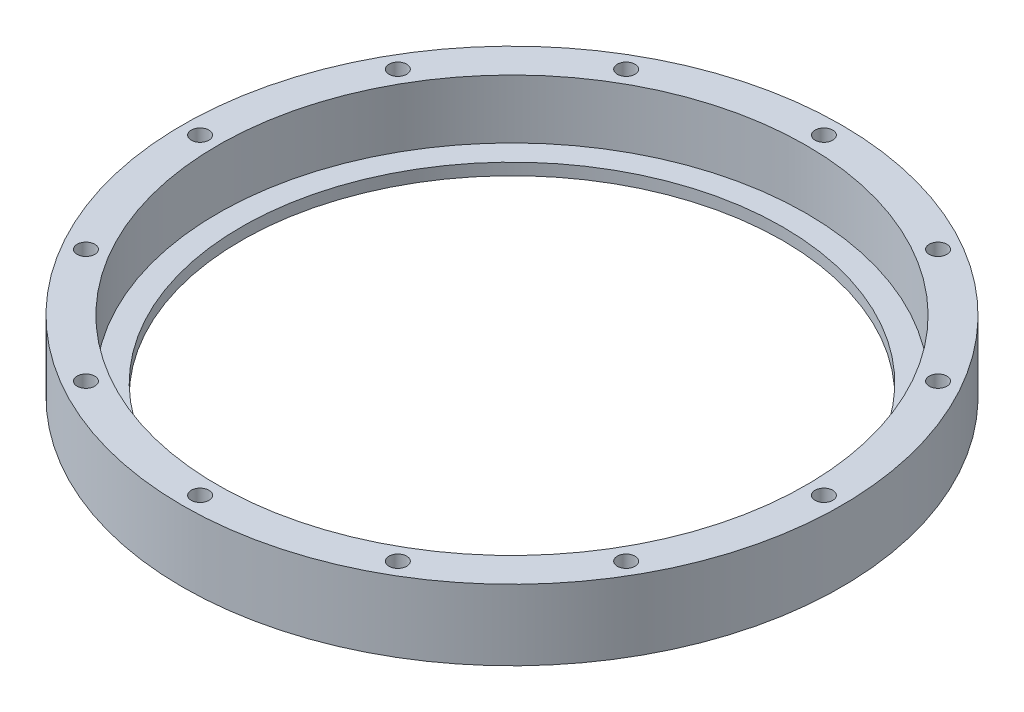
SolidWorks part; units mm, degrees
ref_plane "前视基准面" through (0, 0, 0) normal (0, 0, 1) x (1, 0, 0)
ref_plane "上视基准面" through (0, 0, 0) normal (0, 1, 0) x (1, 0, 0)
ref_plane "右视基准面" through (0, 0, 0) normal (1, 0, 0) x (0, 0, -1)
other "Configuration Table"
sketch "草图2" plane through (0, 0, 0) normal (0, 0, 1) x (1, 0, 0)
  line L0 (0, 0) -> (46, 0) construction
  line L1 (46, 0) -> (46, 2)
  line L2 (46, 2) -> (50, 2)
  line L3 (50, 2) -> (50, 12)
  line L4 (50, 12) -> (56, 12)
  line L5 (56, 12) -> (56, 0)
  line L6 (56, 0) -> (46, 0)
  line L7 (0, 0) -> (0, 12) construction
  line L8 (0, 12) -> (50, 12) construction
  dimension "D1" = 6
  dimension "D2" = 4
  dimension "D3" = 10
  dimension "D4" = 2
  dimension "D5" = 50
revolve "旋转1" add sketch "草图2" angle 360 about L7
sketch "草图3" plane through (0, 0, 0) normal (0, 1, 0) x (1, 0, 0)
  line L0 (0, 56) -> (0, 50) construction
  circle A0 centre (0, 0) radius 56 construction
  circle A1 centre (0, 0) radius 50 construction
  circle A2 centre (0, 53) radius 1.5
  circle A3 centre (26.5, 45.8993) radius 1.5
  circle A4 centre (45.8993, 26.5) radius 1.5
  circle A5 centre (53, 0) radius 1.5
  circle A6 centre (45.8993, -26.5) radius 1.5
  circle A7 centre (26.5, -45.8993) radius 1.5
  circle A8 centre (0, -53) radius 1.5
  circle A9 centre (-26.5, -45.8993) radius 1.5
  circle A10 centre (-45.8993, -26.5) radius 1.5
  circle A11 centre (-53, 0) radius 1.5
  circle A12 centre (-45.8993, 26.5) radius 1.5
  circle A13 centre (-26.5, 45.8993) radius 1.5
  point P33 (0, 0)
  dimension "D1" = 3
  dimension "D2" = 12
extrude "切除-拉伸3" cut sketch "草图3" along normal through all
